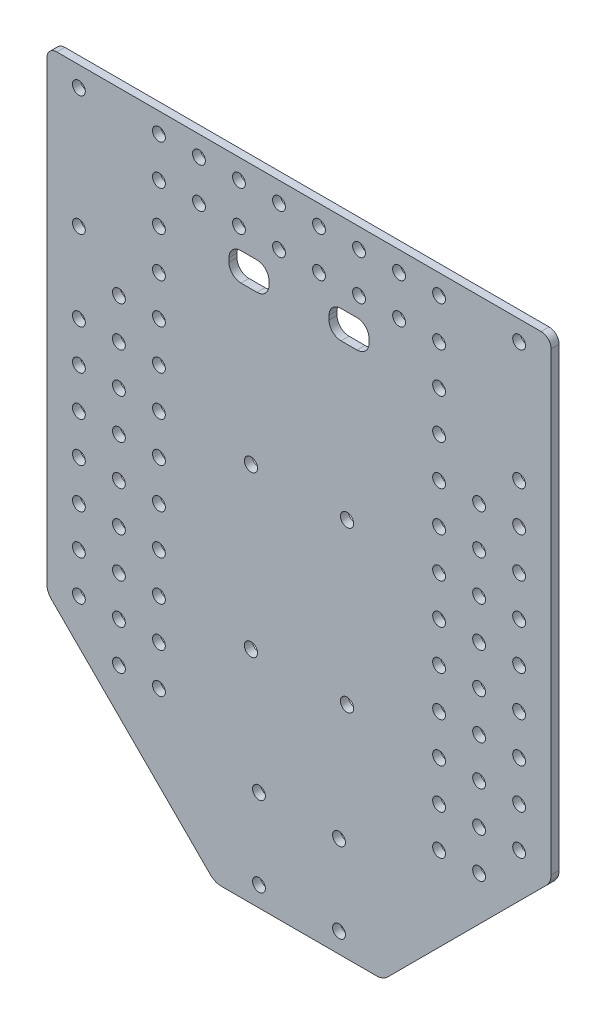
SolidWorks part; units mm, degrees
ref_plane "Front" through (0, 0, 0) normal (0, 0, 1) x (1, 0, 0)
ref_plane "Top" through (0, 0, 0) normal (0, 1, 0) x (1, 0, 0)
ref_plane "Right" through (0, 0, 0) normal (1, 0, 0) x (0, 0, -1)
sketch "Эскиз1" plane through (0, 0, 0) normal (0, 0, 1) x (1, 0, 0)
  line L0 (-63, 0) -> (63, 0)
  line L1 (63, 0) -> (63, -160)
  line L3 (63, -160) -> (-63, -160)
  line L5 (-63, -160) -> (-63, 0)
  point P3 (0, 0)
  point P7 (0, -160)
  dimension "D1" = 126
  dimension "D2" = 160
extrude "Пластина нижняя" add sketch "Эскиз1" along normal blind 2
sketch "Эскиз2" plane through (0, 0, 2) normal (0, 0, 1) x (1, 0, 0)
  line L14 (10, -135) -> (-10, -135) construction
  line L15 (10, -135) -> (10, -155) construction
  line L16 (10, -155) -> (-10, -155) construction
  line L17 (-10, -135) -> (-10, -155) construction
  line L18 (-63, -160) -> (63, -160) construction
  circle A8 centre (10, -135) radius 1.6
  circle A9 centre (-10, -135) radius 1.6
  circle A10 centre (-10, -155) radius 1.6
  circle A11 centre (10, -155) radius 1.6
  point P7 (0, -135)
  dimension "D4" = 3.2
  dimension "D2" = 20
  dimension "D3" = 5
extrude "Крепление_заднего_колеса" cut sketch "Эскиз2" against normal up to next
sketch "Эскиз3" plane through (0, 0, 0) normal (0, 0, -1) x (-1, 0, 0)
  line L1 (-12, -65) -> (12, -65) construction
  line L2 (-12, -65) -> (-12, -105) construction
  line L3 (-12, -105) -> (12, -105) construction
  line L4 (12, -65) -> (12, -105) construction
  line L5 (63, -160) -> (-63, -160) construction
  circle A0 centre (-12, -65) radius 1.65
  circle A1 centre (12, -65) radius 1.65
  circle A2 centre (12, -105) radius 1.65
  circle A3 centre (-12, -105) radius 1.65
  point P8 (0, -65)
  dimension "D3" = 3.3
  dimension "D1" = 40
  dimension "D2" = 24
  dimension "D4" = 55
extrude "Крепление батареи" cut sketch "Эскиз3" against normal through all
chamfer "Фаска2" distance 42 1 edges at (-63, -160, 1)
chamfer "Фаска1" distance 42 1 edges at (63, -160, 1)
fillet "Скругление1" radius 4 4 edges at (63, -118, 1) (-63, -118, 1) (-21, -160, 1) (21, -160, 1)
sketch "Эскиз6" plane through (0, 0, 0) normal (0, 0, -1) x (-1, 0, 0)
  line L0 (-63, 0) -> (63, 0) construction
  line L1 (-17.5, -20) -> (-7.5, -20)
  line L2 (-17.5, -20) -> (-17.5, -27)
  line L3 (-17.5, -27) -> (-7.5, -27)
  line L4 (-7.5, -20) -> (-7.5, -27)
  line L5 (0, 0) -> (0, -160) construction
  line L6 (19.3431, -160) -> (-19.3431, -160) construction
  line L7 (7.5, -20) -> (7.5, -27)
  line L8 (17.5, -27) -> (7.5, -27)
  line L9 (17.5, -20) -> (17.5, -27)
  line L10 (17.5, -20) -> (7.5, -20)
  dimension "D1" = 7
  dimension "D2" = 10
  dimension "D3" = 20
  dimension "D4" = 7.5
extrude "Под провода двигателей" cut sketch "Эскиз6" against normal through all
sketch "Эскиз4" plane through (0, 0, 0) normal (0, 0, -1) x (-1, 0, 0)
  line L0 (0, 0) -> (0, -160) construction
  line L1 (-63, 0) -> (63, 0) construction
  line L2 (19.3431, -160) -> (-19.3431, -160) construction
  circle A0 centre (5, -155) radius 1.6 construction
  circle A2 centre (15, -155) radius 1.6 construction
  circle A3 centre (25, -155) radius 1.6 construction
  circle A4 centre (35, -155) radius 1.6 construction
  circle A5 centre (45, -155) radius 1.6 construction
  circle A6 centre (55, -155) radius 1.6 construction
  circle A7 centre (65, -155) radius 1.6 construction
  circle A8 centre (-65, -155) radius 1.6 construction
  circle A9 centre (-55, -155) radius 1.6 construction
  circle A10 centre (-45, -155) radius 1.6 construction
  circle A11 centre (-35, -155) radius 1.6 construction
  circle A12 centre (-25, -155) radius 1.6 construction
  circle A13 centre (-15, -155) radius 1.6 construction
  circle A14 centre (-5, -155) radius 1.6 construction
  circle A15 centre (5, -145) radius 1.6 construction
  circle A16 centre (15, -145) radius 1.6 construction
  circle A17 centre (25, -145) radius 1.6 construction
  circle A18 centre (35, -145) radius 1.6 construction
  circle A19 centre (45, -145) radius 1.6 construction
  circle A20 centre (55, -145) radius 1.6 construction
  circle A21 centre (65, -145) radius 1.6 construction
  circle A22 centre (-65, -145) radius 1.6 construction
  circle A23 centre (-55, -145) radius 1.6 construction
  circle A24 centre (-45, -145) radius 1.6 construction
  circle A25 centre (-35, -145) radius 1.6 construction
  circle A26 centre (-25, -145) radius 1.6 construction
  circle A27 centre (-15, -145) radius 1.6 construction
  circle A28 centre (-5, -145) radius 1.6 construction
  circle A29 centre (5, -135) radius 1.6 construction
  circle A30 centre (15, -135) radius 1.6 construction
  circle A31 centre (25, -135) radius 1.6 construction
  circle A32 centre (35, -135) radius 1.6 construction
  circle A33 centre (45, -135) radius 1.6 construction
  circle A34 centre (55, -135) radius 1.6 construction
  circle A35 centre (65, -135) radius 1.6 construction
  circle A36 centre (-65, -135) radius 1.6 construction
  circle A37 centre (-55, -135) radius 1.6 construction
  circle A38 centre (-45, -135) radius 1.6 construction
  circle A39 centre (-35, -135) radius 1.6 construction
  circle A40 centre (-25, -135) radius 1.6 construction
  circle A41 centre (-15, -135) radius 1.6 construction
  circle A42 centre (-5, -135) radius 1.6 construction
  circle A43 centre (5, -125) radius 1.6 construction
  circle A44 centre (15, -125) radius 1.6 construction
  circle A45 centre (25, -125) radius 1.6 construction
  circle A46 centre (35, -125) radius 1.6
  circle A47 centre (45, -125) radius 1.6
  circle A48 centre (55, -125) radius 1.6 construction
  circle A49 centre (65, -125) radius 1.6 construction
  circle A50 centre (-65, -125) radius 1.6 construction
  circle A51 centre (-55, -125) radius 1.6 construction
  circle A52 centre (-45, -125) radius 1.6
  circle A53 centre (-35, -125) radius 1.6
  circle A54 centre (-25, -125) radius 1.6 construction
  circle A55 centre (-15, -125) radius 1.6 construction
  circle A56 centre (-5, -125) radius 1.6 construction
  circle A57 centre (5, -115) radius 1.6 construction
  circle A58 centre (15, -115) radius 1.6 construction
  circle A59 centre (25, -115) radius 1.6 construction
  circle A60 centre (35, -115) radius 1.6
  circle A61 centre (45, -115) radius 1.6
  circle A62 centre (55, -115) radius 1.6
  circle A63 centre (65, -115) radius 1.6 construction
  circle A64 centre (-65, -115) radius 1.6 construction
  circle A65 centre (-55, -115) radius 1.6
  circle A66 centre (-45, -115) radius 1.6
  circle A67 centre (-35, -115) radius 1.6
  circle A68 centre (-25, -115) radius 1.6 construction
  circle A69 centre (-15, -115) radius 1.6 construction
  circle A70 centre (-5, -115) radius 1.6 construction
  circle A71 centre (5, -105) radius 1.6 construction
  circle A72 centre (15, -105) radius 1.6 construction
  circle A73 centre (25, -105) radius 1.6 construction
  circle A74 centre (35, -105) radius 1.6
  circle A75 centre (45, -105) radius 1.6
  circle A76 centre (55, -105) radius 1.6
  circle A77 centre (65, -105) radius 1.6 construction
  circle A78 centre (-65, -105) radius 1.6 construction
  circle A79 centre (-55, -105) radius 1.6
  circle A80 centre (-45, -105) radius 1.6
  circle A81 centre (-35, -105) radius 1.6
  circle A82 centre (-25, -105) radius 1.6 construction
  circle A83 centre (-15, -105) radius 1.6 construction
  circle A84 centre (-5, -105) radius 1.6 construction
  circle A85 centre (5, -95) radius 1.6 construction
  circle A86 centre (15, -95) radius 1.6 construction
  circle A87 centre (25, -95) radius 1.6 construction
  circle A88 centre (35, -95) radius 1.6
  circle A89 centre (45, -95) radius 1.6
  circle A90 centre (55, -95) radius 1.6
  circle A91 centre (65, -95) radius 1.6 construction
  circle A92 centre (-65, -95) radius 1.6 construction
  circle A93 centre (-55, -95) radius 1.6
  circle A94 centre (-45, -95) radius 1.6
  circle A95 centre (-35, -95) radius 1.6
  circle A96 centre (-25, -95) radius 1.6 construction
  circle A97 centre (-15, -95) radius 1.6 construction
  circle A98 centre (-5, -95) radius 1.6 construction
  circle A99 centre (5, -85) radius 1.6 construction
  circle A100 centre (15, -85) radius 1.6 construction
  circle A101 centre (25, -85) radius 1.6 construction
  circle A102 centre (35, -85) radius 1.6
  circle A103 centre (45, -85) radius 1.6
  circle A104 centre (55, -85) radius 1.6
  circle A105 centre (65, -85) radius 1.6 construction
  circle A106 centre (-65, -85) radius 1.6 construction
  circle A107 centre (-55, -85) radius 1.6
  circle A108 centre (-45, -85) radius 1.6
  circle A109 centre (-35, -85) radius 1.6
  circle A110 centre (-25, -85) radius 1.6 construction
  circle A111 centre (-15, -85) radius 1.6 construction
  circle A112 centre (-5, -85) radius 1.6 construction
  circle A113 centre (5, -75) radius 1.6 construction
  circle A114 centre (15, -75) radius 1.6 construction
  circle A115 centre (25, -75) radius 1.6 construction
  circle A116 centre (35, -75) radius 1.6
  circle A117 centre (45, -75) radius 1.6
  circle A118 centre (55, -75) radius 1.6
  circle A119 centre (65, -75) radius 1.6 construction
  circle A120 centre (-65, -75) radius 1.6 construction
  circle A121 centre (-55, -75) radius 1.6
  circle A122 centre (-45, -75) radius 1.6
  circle A123 centre (-35, -75) radius 1.6
  circle A124 centre (-25, -75) radius 1.6 construction
  circle A125 centre (-15, -75) radius 1.6 construction
  circle A126 centre (-5, -75) radius 1.6 construction
  circle A127 centre (5, -65) radius 1.6 construction
  circle A128 centre (15, -65) radius 1.6 construction
  circle A129 centre (25, -65) radius 1.6 construction
  circle A130 centre (35, -65) radius 1.6
  circle A131 centre (45, -65) radius 1.6
  circle A132 centre (55, -65) radius 1.6
  circle A133 centre (65, -65) radius 1.6 construction
  circle A134 centre (-65, -65) radius 1.6 construction
  circle A135 centre (-55, -65) radius 1.6
  circle A136 centre (-45, -65) radius 1.6
  circle A137 centre (-35, -65) radius 1.6
  circle A138 centre (-25, -65) radius 1.6 construction
  circle A139 centre (-15, -65) radius 1.6 construction
  circle A140 centre (-5, -65) radius 1.6 construction
  circle A141 centre (5, -55) radius 1.6 construction
  circle A142 centre (15, -55) radius 1.6 construction
  circle A143 centre (25, -55) radius 1.6 construction
  circle A144 centre (35, -55) radius 1.6
  circle A145 centre (45, -55) radius 1.6
  circle A146 centre (55, -55) radius 1.6
  circle A147 centre (65, -55) radius 1.6 construction
  circle A148 centre (-65, -55) radius 1.6 construction
  circle A149 centre (-55, -55) radius 1.6
  circle A150 centre (-45, -55) radius 1.6
  circle A151 centre (-35, -55) radius 1.6
  circle A152 centre (-25, -55) radius 1.6 construction
  circle A153 centre (-15, -55) radius 1.6 construction
  circle A154 centre (-5, -55) radius 1.6 construction
  circle A155 centre (5, -45) radius 1.6 construction
  circle A156 centre (15, -45) radius 1.6 construction
  circle A157 centre (25, -45) radius 1.6 construction
  circle A158 centre (35, -45) radius 1.6
  circle A159 centre (45, -45) radius 1.6
  circle A160 centre (55, -45) radius 1.6 construction
  circle A161 centre (65, -45) radius 1.6 construction
  circle A162 centre (-65, -45) radius 1.6 construction
  circle A163 centre (-55, -45) radius 1.6
  circle A164 centre (-45, -45) radius 1.6
  circle A165 centre (-35, -45) radius 1.6
  circle A166 centre (-25, -45) radius 1.6 construction
  circle A167 centre (-15, -45) radius 1.6 construction
  circle A168 centre (-5, -45) radius 1.6 construction
  circle A169 centre (5, -35) radius 1.6 construction
  circle A170 centre (15, -35) radius 1.6 construction
  circle A171 centre (25, -35) radius 1.6 construction
  circle A172 centre (35, -35) radius 1.6
  circle A173 centre (45, -35) radius 1.6 construction
  circle A174 centre (55, -35) radius 1.6
  circle A175 centre (65, -35) radius 1.6 construction
  circle A176 centre (-65, -35) radius 1.6 construction
  circle A177 centre (-55, -35) radius 1.6
  circle A178 centre (-45, -35) radius 1.6 construction
  circle A179 centre (-35, -35) radius 1.6
  circle A180 centre (-25, -35) radius 1.6 construction
  circle A181 centre (-15, -35) radius 1.6 construction
  circle A182 centre (-5, -35) radius 1.6 construction
  circle A183 centre (5, -25) radius 1.6 construction
  circle A184 centre (15, -25) radius 1.6 construction
  circle A185 centre (25, -25) radius 1.6 construction
  circle A186 centre (35, -25) radius 1.6
  circle A187 centre (45, -25) radius 1.6 construction
  circle A188 centre (55, -25) radius 1.6 construction
  circle A189 centre (65, -25) radius 1.6 construction
  circle A190 centre (-65, -25) radius 1.6 construction
  circle A191 centre (-55, -25) radius 1.6 construction
  circle A192 centre (-45, -25) radius 1.6 construction
  circle A193 centre (-35, -25) radius 1.6
  circle A194 centre (-25, -25) radius 1.6 construction
  circle A195 centre (-15, -25) radius 1.6 construction
  circle A196 centre (-5, -25) radius 1.6 construction
  circle A197 centre (5, -15) radius 1.6
  circle A198 centre (15, -15) radius 1.6
  circle A199 centre (25, -15) radius 1.6
  circle A200 centre (35, -15) radius 1.6
  circle A201 centre (45, -15) radius 1.6 construction
  circle A202 centre (55, -15) radius 1.6 construction
  circle A203 centre (65, -15) radius 1.6 construction
  circle A204 centre (-65, -15) radius 1.6 construction
  circle A205 centre (-55, -15) radius 1.6 construction
  circle A206 centre (-45, -15) radius 1.6 construction
  circle A207 centre (-35, -15) radius 1.6
  circle A208 centre (-25, -15) radius 1.6
  circle A209 centre (-15, -15) radius 1.6
  circle A210 centre (-5, -15) radius 1.6
  circle A211 centre (5, -5) radius 1.6
  circle A212 centre (15, -5) radius 1.6
  circle A213 centre (25, -5) radius 1.6
  circle A214 centre (35, -5) radius 1.6
  circle A215 centre (45, -5) radius 1.6 construction
  circle A216 centre (55, -5) radius 1.6
  circle A217 centre (65, -5) radius 1.6 construction
  circle A218 centre (-65, -5) radius 1.6 construction
  circle A219 centre (-55, -5) radius 1.6
  circle A220 centre (-45, -5) radius 1.6 construction
  circle A221 centre (-35, -5) radius 1.6
  circle A222 centre (-25, -5) radius 1.6
  circle A223 centre (-15, -5) radius 1.6
  circle A224 centre (-5, -5) radius 1.6
  circle A225 centre (5, 5) radius 1.6 construction
  circle A226 centre (15, 5) radius 1.6 construction
  circle A227 centre (25, 5) radius 1.6 construction
  circle A228 centre (35, 5) radius 1.6 construction
  circle A229 centre (45, 5) radius 1.6 construction
  circle A230 centre (55, 5) radius 1.6 construction
  circle A231 centre (65, 5) radius 1.6 construction
  circle A232 centre (-65, 5) radius 1.6 construction
  circle A233 centre (-55, 5) radius 1.6 construction
  circle A234 centre (-45, 5) radius 1.6 construction
  circle A235 centre (-35, 5) radius 1.6 construction
  circle A236 centre (-25, 5) radius 1.6 construction
  circle A237 centre (-15, 5) radius 1.6 construction
  circle A238 centre (-5, 5) radius 1.6 construction
  circle A239 centre (5, 15) radius 1.6 construction
  circle A240 centre (15, 15) radius 1.6 construction
  circle A241 centre (25, 15) radius 1.6 construction
  circle A242 centre (35, 15) radius 1.6 construction
  circle A243 centre (45, 15) radius 1.6 construction
  circle A244 centre (55, 15) radius 1.6 construction
  circle A245 centre (65, 15) radius 1.6 construction
  circle A246 centre (-65, 15) radius 1.6 construction
  circle A247 centre (-55, 15) radius 1.6 construction
  circle A248 centre (-45, 15) radius 1.6 construction
  circle A249 centre (-35, 15) radius 1.6 construction
  circle A250 centre (-25, 15) radius 1.6 construction
  circle A251 centre (-15, 15) radius 1.6 construction
  circle A252 centre (-5, 15) radius 1.6 construction
  circle A253 centre (5, 25) radius 1.6 construction
  circle A254 centre (15, 25) radius 1.6 construction
  circle A255 centre (25, 25) radius 1.6 construction
  circle A256 centre (35, 25) radius 1.6 construction
  circle A257 centre (45, 25) radius 1.6 construction
  circle A258 centre (55, 25) radius 1.6 construction
  circle A259 centre (65, 25) radius 1.6 construction
  circle A260 centre (-65, 25) radius 1.6 construction
  circle A261 centre (-55, 25) radius 1.6 construction
  circle A262 centre (-45, 25) radius 1.6 construction
  circle A263 centre (-35, 25) radius 1.6 construction
  circle A264 centre (-25, 25) radius 1.6 construction
  circle A265 centre (-15, 25) radius 1.6 construction
  circle A266 centre (-5, 25) radius 1.6 construction
  circle A267 centre (5, 35) radius 1.6 construction
  circle A268 centre (15, 35) radius 1.6 construction
  circle A269 centre (25, 35) radius 1.6 construction
  circle A270 centre (35, 35) radius 1.6 construction
  circle A271 centre (45, 35) radius 1.6 construction
  circle A272 centre (55, 35) radius 1.6 construction
  circle A273 centre (65, 35) radius 1.6 construction
  circle A274 centre (-65, 35) radius 1.6 construction
  circle A275 centre (-55, 35) radius 1.6 construction
  circle A276 centre (-45, 35) radius 1.6 construction
  circle A277 centre (-35, 35) radius 1.6 construction
  circle A278 centre (-25, 35) radius 1.6 construction
  circle A279 centre (-15, 35) radius 1.6 construction
  circle A280 centre (-5, 35) radius 1.6 construction
  circle A281 centre (5, 45) radius 1.6 construction
  circle A282 centre (15, 45) radius 1.6 construction
  circle A283 centre (25, 45) radius 1.6 construction
  circle A284 centre (35, 45) radius 1.6 construction
  circle A285 centre (45, 45) radius 1.6 construction
  circle A286 centre (55, 45) radius 1.6 construction
  circle A287 centre (65, 45) radius 1.6 construction
  circle A288 centre (-65, 45) radius 1.6 construction
  circle A289 centre (-55, 45) radius 1.6 construction
  circle A290 centre (-45, 45) radius 1.6 construction
  circle A291 centre (-35, 45) radius 1.6 construction
  circle A292 centre (-25, 45) radius 1.6 construction
  circle A293 centre (-15, 45) radius 1.6 construction
  circle A294 centre (-5, 45) radius 1.6 construction
  dimension "D1" = 5
  dimension "D3" = 3.2
  dimension "D2" = 5
  dimension "D5" = 10
  dimension "D7" = 10
  dimension "D4" = 7
  dimension "D6" = 21
extrude "Сетка отв 10х10" cut sketch "Эскиз4" against normal through all
fillet "Скругление2" radius 3 8 edges at (7.5, -27, 1) (7.5, -20, 1) (17.5, -27, 1) (17.5, -20, 1) (-7.5, -27, 1) (-17.5, -27, 1) (-17.5, -20, 1) (-7.5, -20, 1)
fillet "Скругление3" radius 2.5 2 edges at (63, 0, 1) (-63, 0, 1)
